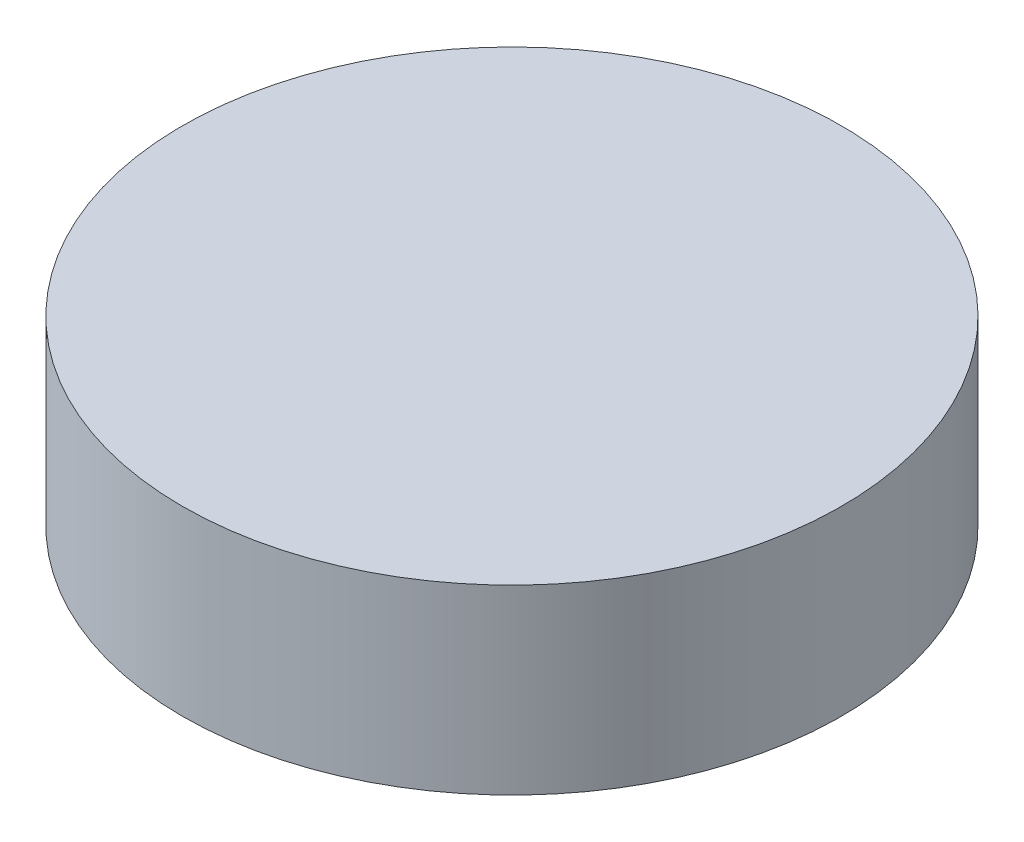
SolidWorks part; units mm, degrees
ref_plane "Front Plane" through (0, 0, 0) normal (0, 0, 1) x (1, 0, 0)
ref_plane "Top Plane" through (0, 0, 0) normal (0, 1, 0) x (1, 0, 0)
ref_plane "Right Plane" through (0, 0, 0) normal (1, 0, 0) x (0, 0, -1)
sketch "Sketch1" plane through (0, 0, 0) normal (0, 1, 0) x (1, 0, 0)
  circle A0 centre (-1.3591, 0.5159) radius 36.83
  point P2 (0, 0)
  dimension "D1" = 73.66
extrude "Boss-Extrude1" add sketch "Sketch1" along normal blind 20.32 contours A0
sketch "Sketch2" plane through (0, 0, 0) normal (0, 1, 0) x (1, 0, 0)
  line L0 (-20.8615, 18.0568) -> (-5.282, 18.0568)
  line L1 (-5.282, 18.0568) -> (16.9104, 18.0568)
  line L2 (16.9104, 18.0568) -> (16.9104, -21.0601)
  line L3 (16.9104, -21.0601) -> (-20.8615, -21.0601)
  line L4 (-20.8615, -21.0601) -> (-20.8615, 17.0481)
